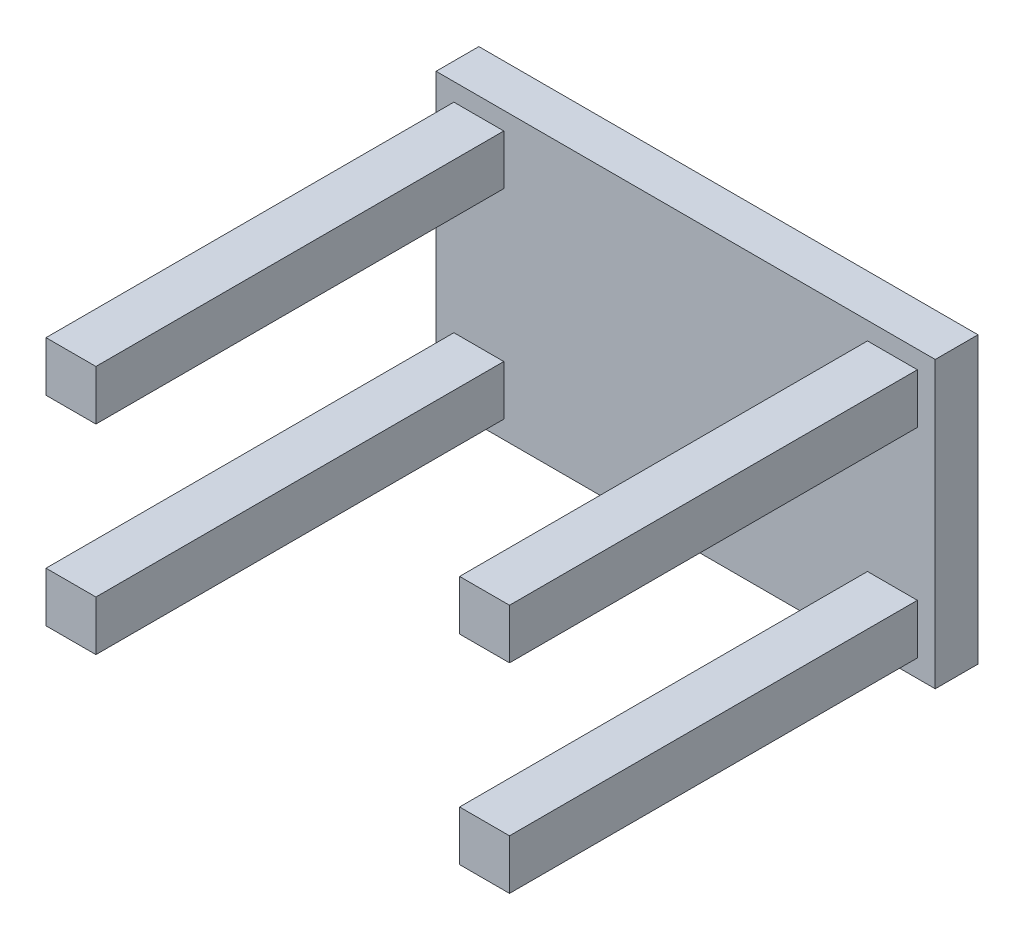
SolidWorks part; units mm, degrees
ref_plane "前视基准面" through (0, 0, 0) normal (0, 0, 1) x (1, 0, 0)
ref_plane "上视基准面" through (0, 0, 0) normal (0, 1, 0) x (1, 0, 0)
ref_plane "右视基准面" through (0, 0, 0) normal (1, 0, 0) x (0, 0, -1)
other "Configuration Table"
sketch "草图1" plane through (0, 0, 0) normal (0, 0, 1) x (1, 0, 0)
  line L1 (-175, -100) -> (175, -100)
  line L2 (-175, -100) -> (-175, 100)
  line L3 (-175, 100) -> (175, 100)
  line L4 (175, -100) -> (175, 100)
  line L5 (-175, -100) -> (175, 100) construction
  line L6 (-175, 100) -> (175, -100) construction
  point P0 (0, 0)
  dimension "D1" = 350
  dimension "D2" = 200
extrude "凸台-拉伸1" add sketch "草图1" along normal blind 30
sketch "草图2" plane through (0, 0, 30) normal (0, 0, 1) x (1, 0, 0)
  line L1 (-145, -70) -> (145, -70) construction
  line L2 (-145, -70) -> (-145, 70) construction
  line L3 (-145, 70) -> (145, 70) construction
  line L4 (145, -70) -> (145, 70) construction
  line L5 (-145, -70) -> (145, 70) construction
  line L6 (-145, 70) -> (145, -70) construction
  line L7 (127.5, 52.5) -> (162.5, 52.5)
  line L8 (127.5, 52.5) -> (127.5, 87.5)
  line L9 (127.5, 87.5) -> (162.5, 87.5)
  line L10 (162.5, 52.5) -> (162.5, 87.5)
  line L11 (127.5, 52.5) -> (162.5, 87.5) construction
  line L12 (127.5, 87.5) -> (162.5, 52.5) construction
  line L13 (127.5, -87.5) -> (162.5, -87.5)
  line L14 (127.5, -87.5) -> (127.5, -52.5)
  line L15 (127.5, -52.5) -> (162.5, -52.5)
  line L16 (162.5, -87.5) -> (162.5, -52.5)
  line L17 (127.5, -87.5) -> (162.5, -52.5) construction
  line L18 (127.5, -52.5) -> (162.5, -87.5) construction
  line L19 (-162.5, -87.5) -> (-127.5, -87.5)
  line L20 (-162.5, -87.5) -> (-162.5, -52.5)
  line L21 (-162.5, -52.5) -> (-127.5, -52.5)
  line L22 (-127.5, -87.5) -> (-127.5, -52.5)
  line L23 (-162.5, -87.5) -> (-127.5, -52.5) construction
  line L24 (-162.5, -52.5) -> (-127.5, -87.5) construction
  line L25 (-162.5, 52.5) -> (-127.5, 52.5)
  line L26 (-162.5, 52.5) -> (-162.5, 87.5)
  line L27 (-162.5, 87.5) -> (-127.5, 87.5)
  line L28 (-127.5, 52.5) -> (-127.5, 87.5)
  line L29 (-162.5, 52.5) -> (-127.5, 87.5) construction
  line L30 (-162.5, 87.5) -> (-127.5, 52.5) construction
  point P0 (0, 0)
  dimension "D1" = 290
  dimension "D2" = 140
  dimension "D3" = 35
  dimension "D4" = 35
extrude "凸台-拉伸2" add sketch "草图2" along normal blind 286
